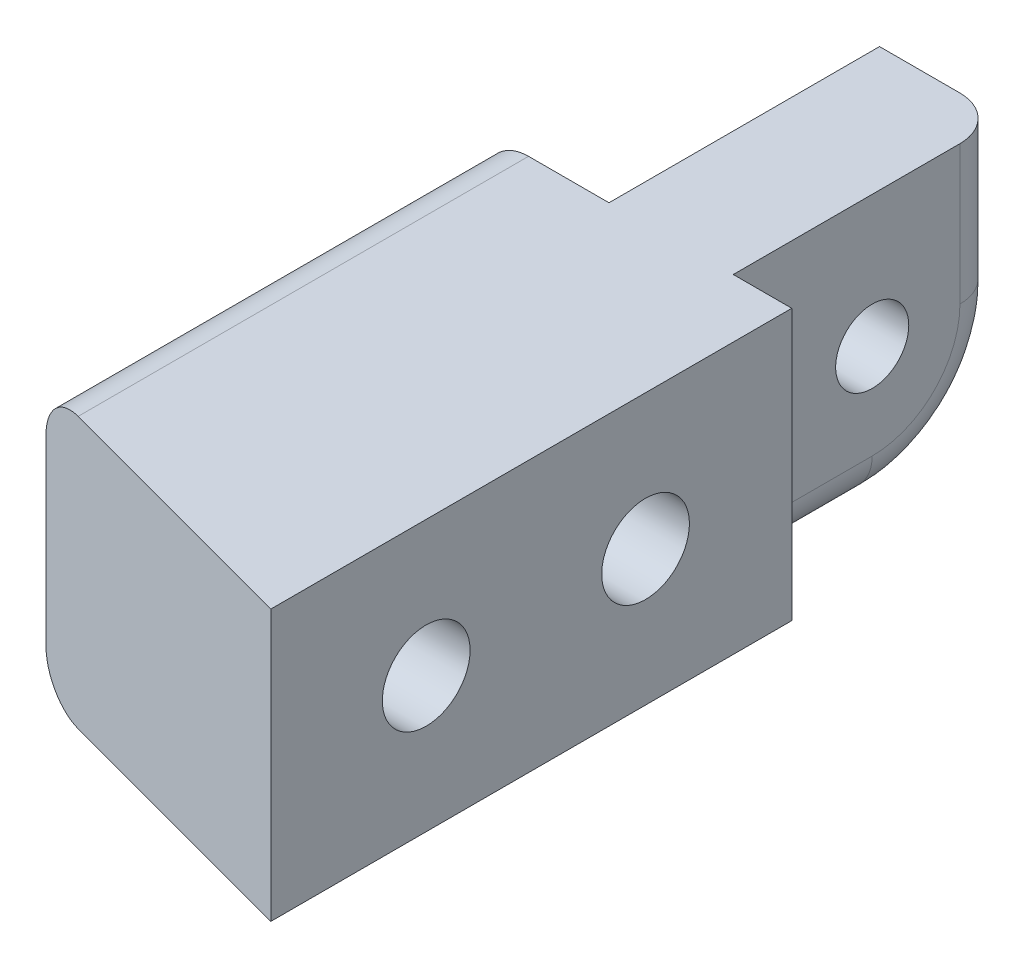
SolidWorks part; units mm, degrees
ref_plane "Front Plane" through (0, 0, 0) normal (0, 0, 1) x (1, 0, 0)
ref_plane "Top Plane" through (0, 0, 0) normal (0, 1, 0) x (1, 0, 0)
ref_plane "Right Plane" through (0, 0, 0) normal (1, 0, 0) x (0, 0, -1)
sketch "Sketch2" plane through (0, 0, 0) normal (0, 1, 0) x (1, 0, 0)
  line L0 (-10.5, 30) -> (-10.5, 0)
  line L1 (-10.5, 0) -> (10.5, -5.6269)
  line L4 (10.5, 30) -> (10.5, -5.6269)
  line L5 (-10.5, 0) -> (10.5, 0) construction
  line L6 (0, 48.5) -> (0, -2.8135) construction
  line L7 (6.5, 30) -> (6.5, 48.5)
  line L8 (6.5, 48.5) -> (-2, 48.5)
  line L9 (-2, 48.5) -> (-2, 30)
  line L10 (-10.5, 30) -> (-2, 30)
  line L11 (6.5, 30) -> (10.5, 30)
  dimension "D1" = 105
  dimension "D2" = 30
  dimension "D3" = 21
  dimension "D4" = 18.5
  dimension "D5" = 4
  dimension "D6" = 8.5
  dimension "D7" = 8.5
extrude "Boss-Extrude1" add sketch "Sketch2" along normal blind 18.5 contours L7 L8 L9 L10 L0 L1 L4 L11
sketch "Sketch3" plane through (6.5, 0, 0) normal (1, 0, 0) x (0, 0, -1)
  line L0 (39.5, 9) -> (39.5, 0) construction
  line L2 (30, 0) -> (48.5, 0) construction
  line L3 (48.5, 9) -> (39.5, 9) construction
  line L4 (48.5, 18.5) -> (48.5, 0) construction
  arc A1 (39.5, 0) -> (48.5, 9) centre (39.5, 9) ccw
  point P12 (39.5, 9)
  dimension "D1" = 9
  dimension "D2" = 9
extrude "Cut-Extrude1" cut sketch "Sketch3" against normal blind 8.5 and the other way through all flip side to cut
fillet "Fillet1" radius 3 3 edges at (6.5, 0, -34.75) (6.5, 2.636, -45.864) (6.5, 13.75, -48.5)
sketch "Sketch4" plane through (0, 0, -48.5) normal (0, 0, -1) x (-1, 0, 0)
  line L0 (-6.5, 18.5) -> (-6.5, 3) construction
  line L2 (-3.5, 0) -> (2, 0) construction
  point P0 (-2.25, 3.5)
  dimension "D1" = 4.25
  dimension "D2" = 3.5
hole_wizard "Ø4.0mm Dowel Hole1" positions "Sketch5" profile "Sketch6" hole size "Ø4.0" standard "DIN"
sketch "Sketch5" plane through (0, 0, -48.5) normal (0, 0, -1) x (-1, 0, 0)
  point P0 (-2.25, 3.5)
sketch "Sketch6" plane through (2.25, 3.5, -48.5) normal (1, 0, 0) x (0, 1, 0)
  line L0 (0, 0) -> (0, 32.7017)
  line L1 (0, 32.7017) -> (2, 31.5)
  line L2 (2, 31.5) -> (2, 0)
  line L5 (2, 0) -> (0, 0)
  line L10 (0, 32.7017) -> (-2, 31.5) construction
  line L11 (0, -6.35) -> (0, 107.95) construction
  dimension "Hole Dia." = 4
  dimension "Hole Depth" = 31.5
  dimension "Drill Angle" = 118
sketch "Sketch8" plane through (0, 0, 0) normal (0, -1, 0) x (1, 0, 0)
  line L0 (0.25, -48.5) -> (4.25, -48.5)
  line L5 (0.25, -48.5) -> (0.25, -31.5)
  line L7 (4.25, -31.5) -> (4.25, -48.5)
  line L8 (3.5, -48.5) -> (-2, -48.5) construction
  line L9 (-2, -39.5) -> (-2, -48.5) construction
  line L10 (2.25, -48.5) -> (2.25, -19) construction
  line L11 (0.25, -22.5) -> (0.25, -19)
  line L12 (4.25, -22.5) -> (4.25, -19)
  line L13 (-10.5, -30) -> (-2, -30) construction
  arc A0 (4.25, -31.5) -> (0.25, -31.5) centre (2.25, -31.5) ccw
  arc A2 (0.25, -22.5) -> (4.25, -22.5) centre (2.25, -22.5) ccw
  arc A4 (4.25, -19) -> (0.25, -19) centre (2.25, -19) ccw
  dimension "D3" = 17
  dimension "D4" = 4
  dimension "D6" = 7.5
  dimension "D1" = 2.25
  dimension "D2" = 4
  dimension "D5" = 3.5
extrude "Cut-Extrude3" cut sketch "Sketch8" against normal blind 3.5
sketch "Sketch9" plane through (10.5, 0, 0) normal (1, 0, 0) x (0, 0, -1)
  line L0 (30, 9.25) -> (-5.6269, 9.25) construction
  line L1 (30, 18.5) -> (30, 0) construction
  line L2 (-5.6269, 18.5) -> (-5.6269, 0) construction
  point P6 (20, 9.25)
  point P7 (5, 9.25)
  dimension "D1" = 10
  dimension "D2" = 15
hole_wizard "Ø6.0mm Dowel Hole1" positions "Sketch10" profile "Sketch11" hole size "Ø6.0" standard "DIN" end condition through all
sketch "Sketch10" plane through (10.5, 0, 0) normal (1, 0, 0) x (0, 0, -1)
  point P0 (20, 9.25)
  point P3 (5, 9.25)
sketch "Sketch11" plane through (10.5, 9.25, -20) normal (0, 1, 0) x (0, 0, -1)
  line L0 (0, 0) -> (0, 21)
  line L1 (0, 21) -> (3, 21)
  line L2 (3, 21) -> (3, 0)
  line L5 (3, 0) -> (0, 0)
  line L11 (0, -6.35) -> (0, 107.95) construction
  dimension "Thru Hole Dia." = 6
  dimension "Thru Hole Depth" = 21
fillet "Fillet3" radius 3 2 edges at (-10.5, 0, -15) (-10.5, 18.5, -15)
sketch "Sketch12" plane through (6.5, 0, 0) normal (1, 0, 0) x (0, 0, -1)
  line L0 (30, 18.5) -> (45.5, 18.5) construction
  line L1 (48.5, 18.5) -> (48.5, 9) construction
  point P0 (39.5, 9.5)
  point P5 (0, 0)
  dimension "D1" = 9
  dimension "D2" = 9
hole_wizard "Ø5.0mm Dowel Hole1" positions "Sketch13" profile "Sketch14" hole size "Ø5.0" standard "DIN" end condition through all
sketch "Sketch13" plane through (6.5, 0, 0) normal (1, 0, 0) x (0, 0, -1)
  point P0 (39.5, 9.5)
sketch "Sketch14" plane through (6.5, 9.5, -39.5) normal (0, 1, 0) x (0, 0, -1)
  line L0 (0, 0) -> (0, 17)
  line L1 (0, 17) -> (2.5, 17)
  line L2 (2.5, 17) -> (2.5, 0)
  line L5 (2.5, 0) -> (0, 0)
  line L11 (0, -6.35) -> (0, 107.95) construction
  dimension "Thru Hole Dia." = 5
  dimension "Thru Hole Depth" = 17
